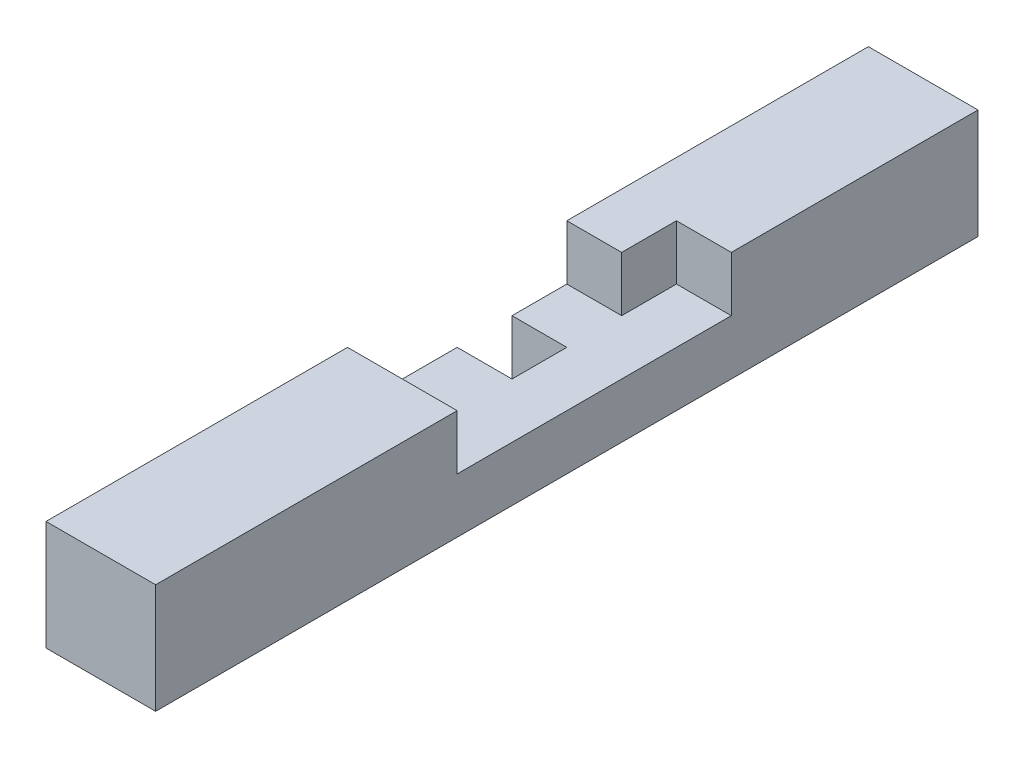
SolidWorks part; units mm, degrees
ref_plane "前基準面" through (0, 0, 0) normal (0, 0, 1) x (1, 0, 0)
ref_plane "上基準面" through (0, 0, 0) normal (0, 1, 0) x (1, 0, 0)
ref_plane "右基準面" through (0, 0, 0) normal (1, 0, 0) x (0, 0, -1)
sketch "草圖1" plane through (0, 0, 0) normal (0, 0, 1) x (1, 0, 0)
  line L1 (-2, 2) -> (2, 2)
  line L2 (-2, 2) -> (-2, -2)
  line L3 (-2, -2) -> (2, -2)
  line L4 (2, 2) -> (2, -2)
  line L5 (-2, 2) -> (2, -2) construction
  line L6 (-2, -2) -> (2, 2) construction
  point P0 (0, 0)
extrude "填料-伸長1" add sketch "草圖1" along normal blind 30 contours L1 L4 L3 L2
sketch "草圖3" plane through (-2, 0, 0) normal (-1, 0, 0) x (0, 0, 1)
  line L0 (30, -2) -> (0, -2) construction
  line L1 (0, 2) -> (9, 2)
  line L2 (0, 2) -> (0, -2)
  line L3 (0, -2) -> (9, -2)
  line L4 (9, 2) -> (9, -2)
sketch "草圖4" plane through (-2, 0, 0) normal (-1, 0, 0) x (0, 0, 1)
  line L1 (9, 2) -> (19, 2)
  line L2 (9, 2) -> (9, 0)
  line L3 (9, 0) -> (19, 0)
  line L4 (19, 2) -> (19, 0)
extrude "除料-伸長1" cut sketch "草圖4" against normal blind 4
sketch "草圖5" plane through (-2, 0, 0) normal (-1, 0, 0) x (0, 0, 1)
  line L0 (30, -2) -> (0, -2) construction
  line L1 (9, 0) -> (11, 0)
  line L2 (9, 0) -> (9, -2)
  line L3 (9, -2) -> (11, -2)
  line L4 (11, 0) -> (11, -2)
sketch "草圖6" plane through (-2, 0, 0) normal (-1, 0, 0) x (0, 0, 1)
  line L0 (30, -2) -> (0, -2) construction
  line L1 (11, 0) -> (15, 0)
  line L2 (11, 0) -> (11, -2)
  line L3 (11, -2) -> (15, -2)
  line L4 (15, 0) -> (15, -2)
extrude "除料-伸長2" cut sketch "草圖6" against normal blind 2 contours L3 L4 L1 L2
sketch "草圖8" plane through (-2, 0, 0) normal (-1, 0, 0) x (0, 0, 1)
  line L1 (9, 2) -> (11, 2)
  line L2 (9, 2) -> (9, 0)
  line L3 (9, 0) -> (11, 0)
  line L4 (11, 2) -> (11, 0)
extrude "填料-伸長4" add sketch "草圖8" against normal blind 2
sketch "草圖10" plane through (0, 0, 11) normal (0, 0, 1) x (1, 0, 0)
  line L1 (0, 0) -> (-2, 0)
  line L2 (0, 0) -> (0, -2)
  line L3 (0, -2) -> (-2, -2)
  line L4 (-2, 0) -> (-2, -2)
extrude "填料-伸長6" add sketch "草圖10" along normal blind 2
